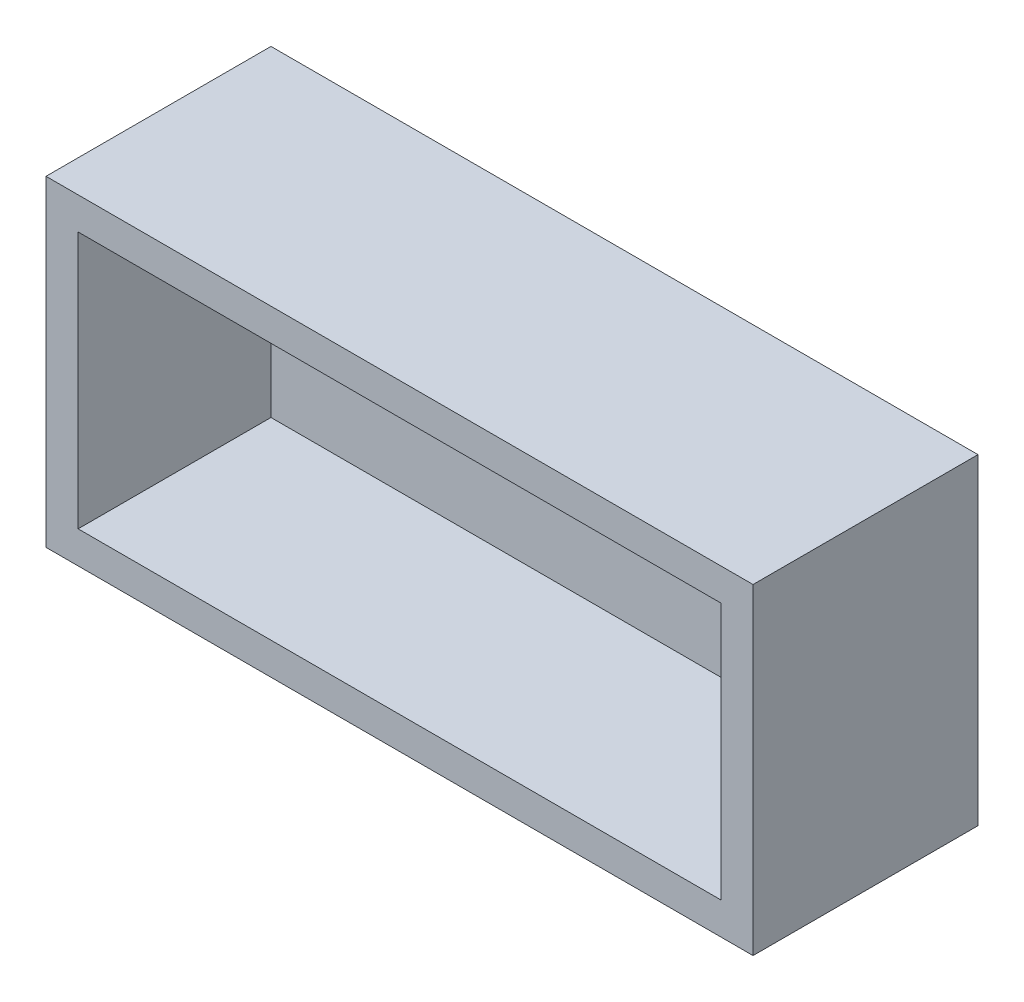
SolidWorks part; units mm, degrees
ref_plane "Alzado" through (0, 0, 0) normal (0, 0, 1) x (1, 0, 0)
ref_plane "Planta" through (0, 0, 0) normal (0, 1, 0) x (1, 0, 0)
ref_plane "Vista lateral" through (0, 0, 0) normal (1, 0, 0) x (0, 0, -1)
sketch "Croquis1" plane through (0, 0, 0) normal (0, 0, 1) x (1, 0, 0)
  line L0 (-52.0901, 27.4354) -> (-22.0901, 27.4354)
  line L1 (-52.0901, 27.4354) -> (-52.0901, 15.4354)
  line L2 (-52.0901, 15.4354) -> (-22.0901, 15.4354)
  line L3 (-22.0901, 15.4354) -> (-22.0901, 27.4354)
  line L4 (-53.5901, 28.9354) -> (-20.5901, 28.9354)
  line L5 (-20.5901, 13.9354) -> (-20.5901, 28.9354)
  line L6 (-53.5901, 13.9354) -> (-20.5901, 13.9354)
  line L7 (-53.5901, 28.9354) -> (-53.5901, 13.9354)
  dimension "D1" = 1.5
extrude "Saliente-Extruir1" add sketch "Croquis1" along normal blind 9
sketch "Croquis2" plane through (0, 0, 0) normal (0, 0, 1) x (1, 0, 0)
  line L4 (-53.5901, 28.9354) -> (-20.5901, 28.9354)
  line L5 (-20.5901, 13.9354) -> (-20.5901, 28.9354)
  line L6 (-53.5901, 13.9354) -> (-20.5901, 13.9354)
  line L7 (-53.5901, 28.9354) -> (-53.5901, 13.9354)
extrude "Saliente-Extruir2" add sketch "Croquis2" against normal blind 1.5
sketch "Croquis3" plane through (0, 0, 0) normal (0, 0, 1) x (1, 0, 0)
  circle A0 centre (-37.0901, 21.4354) radius 1
extrude "Cortar-Extruir1" cut sketch "Croquis3" against normal blind 1.5
